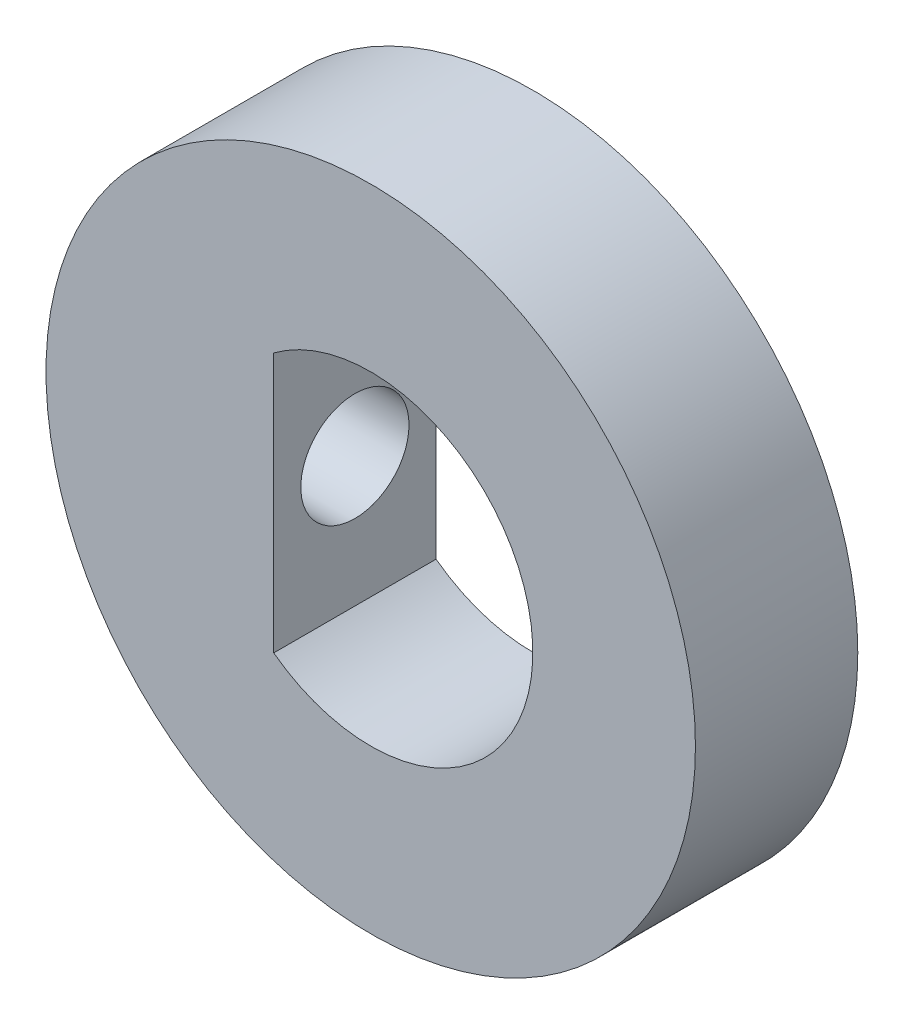
SolidWorks part; units mm, degrees
ref_plane "Plan de face" through (0, 0, 0) normal (0, 0, 1) x (1, 0, 0)
ref_plane "Plan de dessus" through (0, 0, 0) normal (0, 1, 0) x (1, 0, 0)
ref_plane "Plan de droite" through (0, 0, 0) normal (1, 0, 0) x (0, 0, -1)
sketch "Esquisse1" plane through (0, 0, 0) normal (0, 0, 1) x (1, 0, 0)
  line L0 (-1.7923, 2.4) -> (-1.7923, -2.4)
  circle A0 centre (0, 0) radius 6
  circle A1 centre (0, 0) radius 2.9954
extrude "Boss.-Extru.1" add sketch "Esquisse1" along normal blind 3 contours A0 A1 | L0 A1
sketch "Esquisse3" plane through (-1.7923, 0, 0) normal (1, 0, 0) x (0, 0, -1)
  line L2 (-3, 2.4) -> (0, 2.4) construction
  circle A0 centre (-1.5, 0) radius 1
  dimension "D1" = 2
  dimension "D3" = 2.4
  dimension "D2" = 1.5
extrude "Enlèv. mat.-Extru.1" cut sketch "Esquisse3" against normal blind 10
